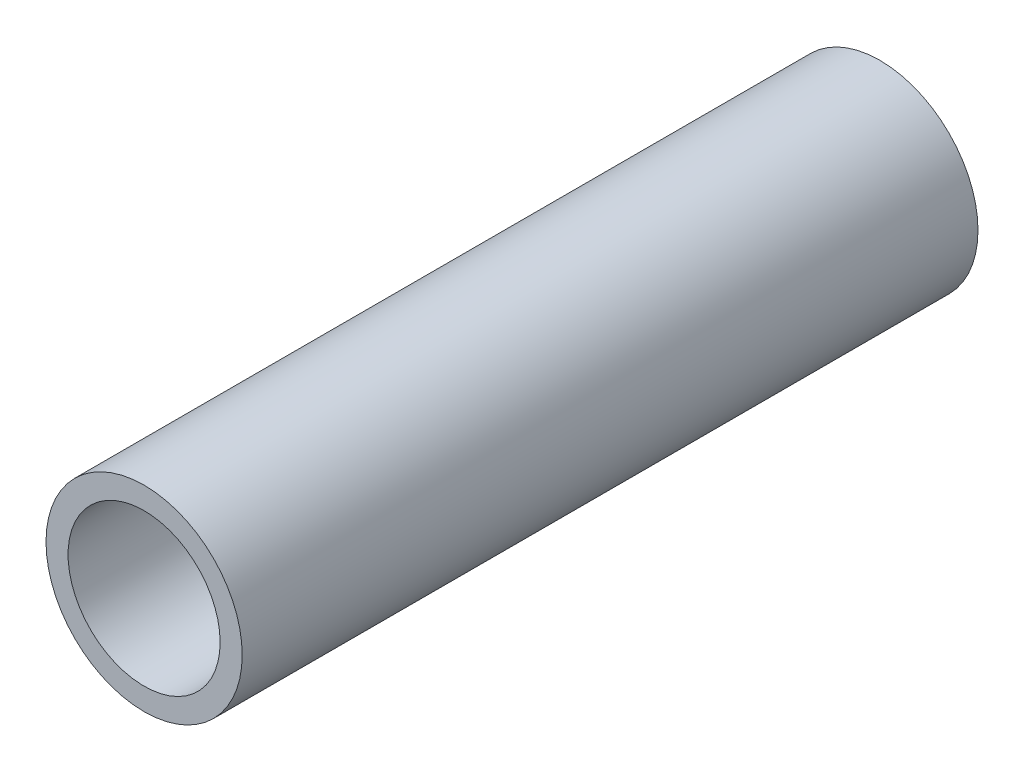
SolidWorks part; units mm, degrees
ref_plane "Спереди" through (0, 0, 0) normal (0, 0, 1) x (1, 0, 0)
ref_plane "Сверху" through (0, 0, 0) normal (0, 1, 0) x (1, 0, 0)
ref_plane "Справа" through (0, 0, 0) normal (1, 0, 0) x (0, 0, -1)
sketch "Эскиз1" plane through (0, 0, 0) normal (0, 0, 1) x (1, 0, 0)
  circle A0 centre (0, 0) radius 1
  circle A1 centre (0, 0) radius 0.775
extrude "Бобышка-Вытянуть1" add sketch "Эскиз1" along normal blind 7.5
